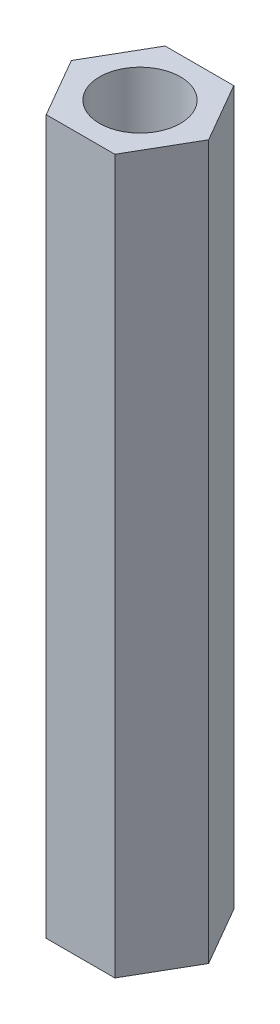
SolidWorks part; units mm, degrees
ref_plane "前视基准面" through (0, 0, 0) normal (0, 0, 1) x (1, 0, 0)
ref_plane "上视基准面" through (0, 0, 0) normal (0, 1, 0) x (1, 0, 0)
ref_plane "右视基准面" through (0, 0, 0) normal (1, 0, 0) x (0, 0, -1)
sketch "草图1" plane through (0, 0, 0) normal (0, 1, 0) x (1, 0, 0)
  line L1 (2.8868, 0) -> (1.4434, 2.5)
  line L2 (1.4434, 2.5) -> (-1.4434, 2.5)
  line L3 (-1.4434, 2.5) -> (-2.8868, 0)
  line L4 (-2.8868, 0) -> (-1.4434, -2.5)
  line L5 (-1.4434, -2.5) -> (1.4434, -2.5)
  line L6 (1.4434, -2.5) -> (2.8868, 0)
  circle A0 centre (0, 0) radius 1.7
  circle A1 centre (0, 0) radius 2.5 construction
  dimension "D1" = 3.4
  dimension "D2" = 5
extrude "凸台-拉伸1" add sketch "草图1" along normal blind 30
equation "\"h3\"= 30'铜柱的长度"
equation "\"D1@凸台-拉伸1\"=\"h3\""
equation "\"d\"= 3'螺丝直径(有补偿)"
equation "\"D1@草图1\"=\"d\"+0.4"
equation "\"h1\"= 10'铜柱的长度"
equation "\"h2\"= 20'铜柱的长度"
